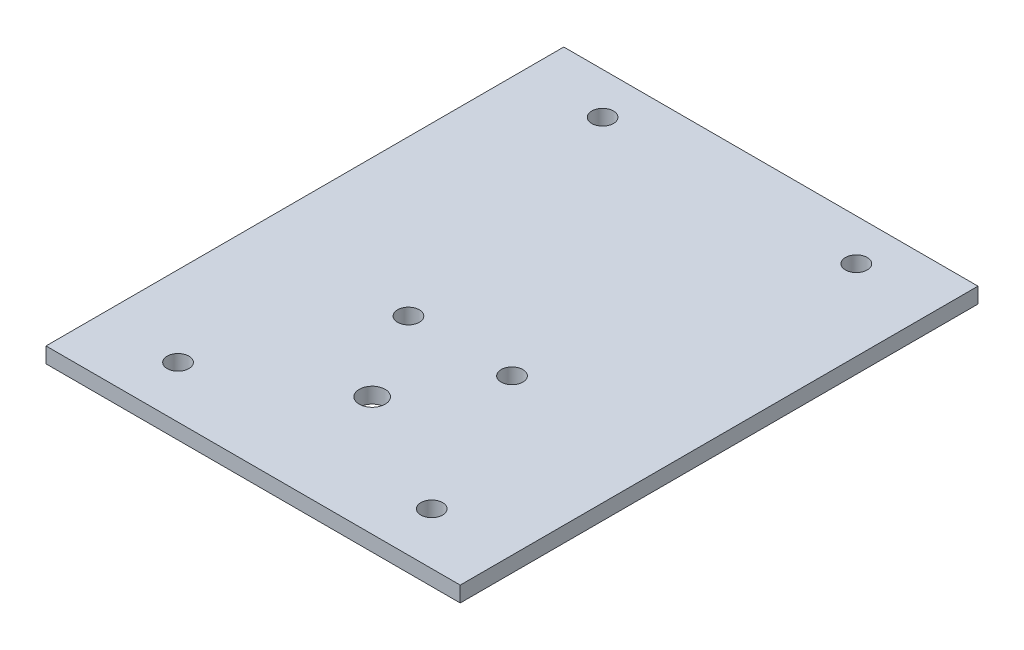
SolidWorks part; units mm, degrees
ref_plane "Front Plane" through (0, 0, 0) normal (0, 0, 1) x (1, 0, 0)
ref_plane "Top Plane" through (0, 0, 0) normal (0, 1, 0) x (1, 0, 0)
ref_plane "Right Plane" through (0, 0, 0) normal (1, 0, 0) x (0, 0, -1)
sketch "Sketch1" plane through (0, 0, 0) normal (0, 1, 0) x (1, 0, 0)
  line L1 (-40, 50) -> (40, 50)
  line L2 (-40, 50) -> (-40, -50)
  line L3 (-40, -50) -> (40, -50)
  line L4 (40, 50) -> (40, -50)
  line L5 (-40, 50) -> (40, -50) construction
  line L6 (-40, -50) -> (40, 50) construction
  circle A0 centre (24.5, 42) radius 2.1
  circle A1 centre (-24.5, 42) radius 2.1
  circle A2 centre (24.5, -40) radius 2.1
  circle A3 centre (-24.5, -40) radius 2.1
  circle A4 centre (10, -10) radius 2.1
  circle A5 centre (-10, -10) radius 2.1
  circle A6 centre (0, -27) radius 2.5
  point P0 (0, 0)
  dimension "D3" = 15.5
  dimension "D4" = 4.2
  dimension "D5" = 8
  dimension "D8" = 4.2
  dimension "D9" = 15.5
  dimension "D10" = 82
  dimension "D6" = 15.5
  dimension "D7" = 8
  dimension "D11" = 82
  dimension "D12" = 15.5
  dimension "D13" = 30
  dimension "D14" = 30
  dimension "D15" = 40
  dimension "D16" = 40
  dimension "D17" = 40
  dimension "D18" = 5
  dimension "D1" = 100
  dimension "D2" = 80
  dimension "D19" = 17
extrude "Boss-Extrude1" add sketch "Sketch1" along normal blind 3
